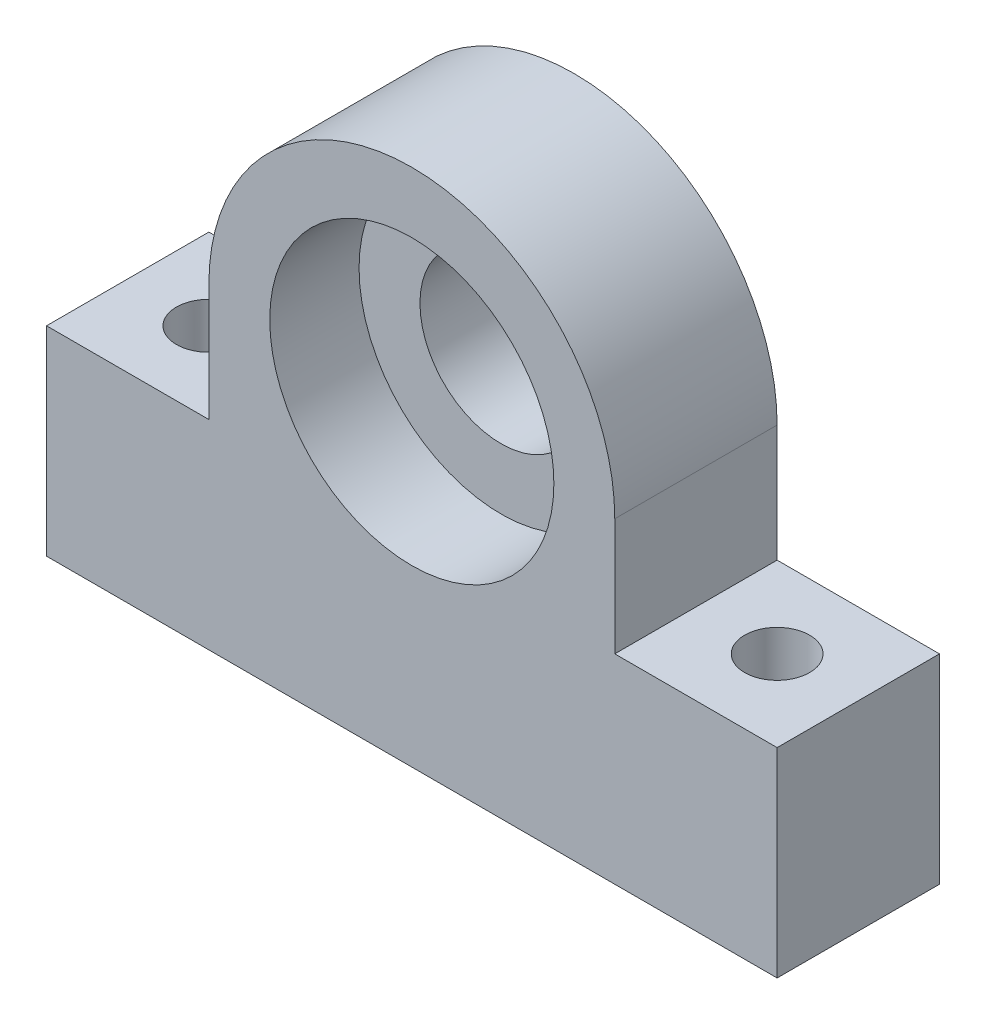
SolidWorks part; units mm, degrees
ref_plane "Front Plane" through (0, 0, 0) normal (0, 0, 1) x (1, 0, 0)
ref_plane "Top Plane" through (0, 0, 0) normal (0, 1, 0) x (1, 0, 0)
ref_plane "Right Plane" through (0, 0, 0) normal (1, 0, 0) x (0, 0, -1)
sketch "Sketch1" plane through (0, 0, 0) normal (0, 0, 1) x (1, 0, 0)
  circle A0 centre (0, 0) radius 25
  circle A1 centre (0, 0) radius 17.5
  dimension "D1" = 50
  dimension "D2" = 35
extrude "Boss-Extrude1" add sketch "Sketch1" along normal blind 20
sketch "Sketch2" plane through (0, 0, 20) normal (0, 0, 1) x (1, 0, 0)
  line L0 (25, 0) -> (25, -14.4113)
  line L1 (25, -14.4113) -> (45, -14.4113)
  line L2 (45, -14.4113) -> (45, -38.9913)
  line L3 (45, -38.9913) -> (-45, -38.9913)
  line L4 (-45, -38.9913) -> (-45, -14.4113)
  line L5 (-45, -14.4113) -> (-25, -14.4113)
  line L6 (-25, -14.4113) -> (-25, 0)
  circle A0 centre (0, 0) radius 25 construction
  arc A1 (-25, 0) -> (25, 0) centre (0, 0) ccw
  dimension "D1" = 20
  dimension "D2" = 24.58
extrude "Boss-Extrude2" add sketch "Sketch2" against normal blind 20
sketch "Sketch3" plane through (0, 0, 0) normal (0, 0, -1) x (-1, 0, 0)
  circle A0 centre (0, 0) radius 10
  circle A1 centre (0, 0) radius 20
  dimension "D1" = 20
  dimension "D2" = 40
extrude "Boss-Extrude3" add sketch "Sketch3" against normal blind 9
sketch "Sketch4" plane through (0, -14.4113, 0) normal (0, 1, 0) x (1, 0, 0)
  line L0 (35, -20) -> (35, 0) construction
  line L1 (45, -20) -> (25, -20) construction
  line L2 (45, 0) -> (25, 0) construction
  line L3 (45, -10) -> (25, -10) construction
  line L4 (45, 0) -> (45, -20) construction
  line L5 (25, 0) -> (25, -20) construction
  line L6 (0, 0) -> (0, -38.904) construction
  line L7 (-45, -10) -> (-25, -10) construction
  line L8 (-35, -20) -> (-35, 0) construction
  circle A0 centre (35, -10) radius 4
  circle A1 centre (-35, -10) radius 4
  dimension "D1" = 8
extrude "Cut-Extrude1" cut sketch "Sketch4" against normal blind 30
